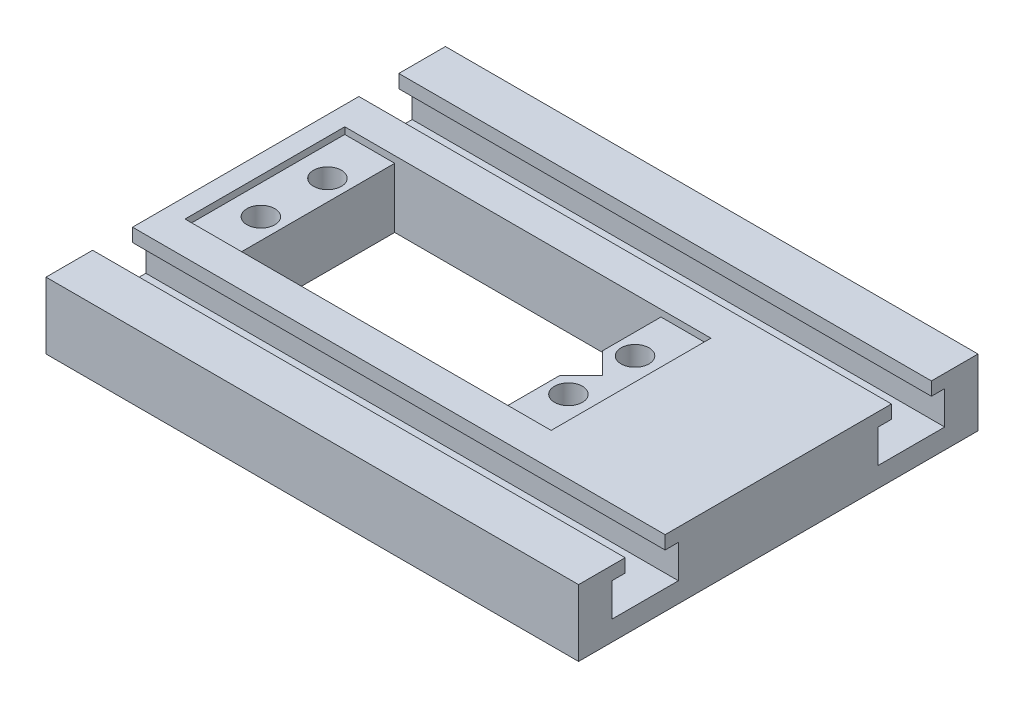
SolidWorks part; units mm, degrees
ref_plane "前基準面" through (0, 0, 0) normal (0, 0, 1) x (1, 0, 0)
ref_plane "上基準面" through (0, 0, 0) normal (0, 1, 0) x (1, 0, 0)
ref_plane "右基準面" through (0, 0, 0) normal (1, 0, 0) x (0, 0, -1)
sketch "草圖1" plane through (0, 0, 0) normal (0, 1, 0) x (1, 0, 0)
  line L1 (-29.62, 12) -> (10.38, 12)
  line L2 (-29.62, 12) -> (-29.62, -12)
  line L3 (-29.62, -12) -> (10.38, -12)
  line L4 (10.38, 12) -> (10.38, -12)
  line L5 (-40, 30) -> (40, 30)
  line L6 (-40, 30) -> (-40, -30)
  line L7 (-40, -30) -> (40, -30)
  line L8 (40, 30) -> (40, -30)
  circle A0 centre (0, 0) radius 1.6622
  circle A1 centre (13.48, 5) radius 2.1
  circle A2 centre (13.48, -5) radius 2.1
  circle A3 centre (-32.72, 5) radius 2.1
  circle A4 centre (-32.72, -5) radius 2.1
  dimension "D4" = 4.2
  dimension "D5" = 4.2
  dimension "D6" = 4.2
  dimension "D7" = 4.2
  dimension "D1" = 10
  dimension "D2" = 13.48
  dimension "D3" = 5
  dimension "D8" = 46.2
  dimension "D9" = 46.2
  dimension "D10" = 40
  dimension "D11" = 3.1
  dimension "D12" = 24
  dimension "D13" = 12
  dimension "D14" = 30
  dimension "D15" = 30
  dimension "D16" = 40
  dimension "D17" = 40
extrude "填料-伸長1" add sketch "草圖1" along normal blind 10 contours L8 L5 L6 L7 A4 A3 A2 A1 L1 L4 L3 L2
ref_plane "平面1" through (40, 10, 30) normal (0, 0, 1) x (1, 0, 0)
sketch "草圖4" plane through (40, 0, 0) normal (1, 0, 0) x (0, 0, -1)
  line L0 (-23, 10) -> (-23, 8)
  line L1 (30, 10) -> (-30, 10) construction
  line L2 (-23, 8) -> (-25, 8)
  line L3 (-25, 8) -> (-25, 3)
  line L4 (-25, 3) -> (-15, 3)
  line L5 (-15, 3) -> (-15, 8)
  line L6 (-15, 8) -> (-17, 8)
  line L7 (-17, 8) -> (-17, 10)
  line L8 (-23, 10) -> (-17, 10)
  line L9 (17, 10) -> (17, 8)
  line L10 (17, 8) -> (15, 8)
  line L11 (15, 8) -> (15, 3)
  line L12 (15, 3) -> (25, 3)
  line L13 (25, 3) -> (25, 8)
  line L14 (25, 8) -> (23, 8)
  line L15 (23, 8) -> (23, 10)
  line L16 (23, 10) -> (17, 10)
  line L17 (30, 0) -> (-30, 0) construction
  line L18 (30, 10) -> (30, 0) construction
  line L19 (-30, 10) -> (-30, 0) construction
  point P22 (-25, 5.5)
  dimension "D1" = 10
  dimension "D2" = 10
  dimension "D3" = 2
  dimension "D4" = 2
  dimension "D5" = 2
  dimension "D6" = 2
  dimension "D7" = 3
  dimension "D8" = 3
  dimension "D9" = 5
  dimension "D10" = 5
  dimension "D11" = 5
  dimension "D12" = 5
  dimension "D13" = 5
  dimension "D14" = 5
extrude "除料-伸長1" cut sketch "草圖4" against normal blind 80
sketch "草圖5" plane through (0, 10, 0) normal (0, 1, 0) x (1, 0, 0)
  line L0 (10.38, 3.25) -> (13.63, 0)
  line L1 (10.38, 12) -> (10.38, -12) construction
  line L2 (13.63, 0) -> (10.38, -3.25)
  line L3 (10.38, -3.25) -> (10.38, 3.25)
  circle A0 centre (13.48, 5) radius 2.1 construction
  dimension "D3" = 5
  dimension "D1" = 315
  dimension "D2" = 270
  dimension "D4" = 6.5
extrude "除料-伸長2" cut sketch "草圖5" against normal blind 80
sketch "草圖7" plane through (0, 10, 0) normal (0, 1, 0) x (1, 0, 0)
  line L1 (-37.12, 12) -> (17.88, 12)
  line L2 (-37.12, 12) -> (-37.12, -12)
  line L3 (-37.12, -12) -> (17.88, -12)
  line L4 (17.88, 12) -> (17.88, -12)
  circle A0 centre (13.48, -5) radius 2.1 construction
  dimension "D1" = 24
  dimension "D2" = 12
  dimension "D3" = 55
  dimension "D4" = 4.4
extrude "除料-伸長3" cut sketch "草圖7" against normal blind 1 contours L1 L4 L3 L2
